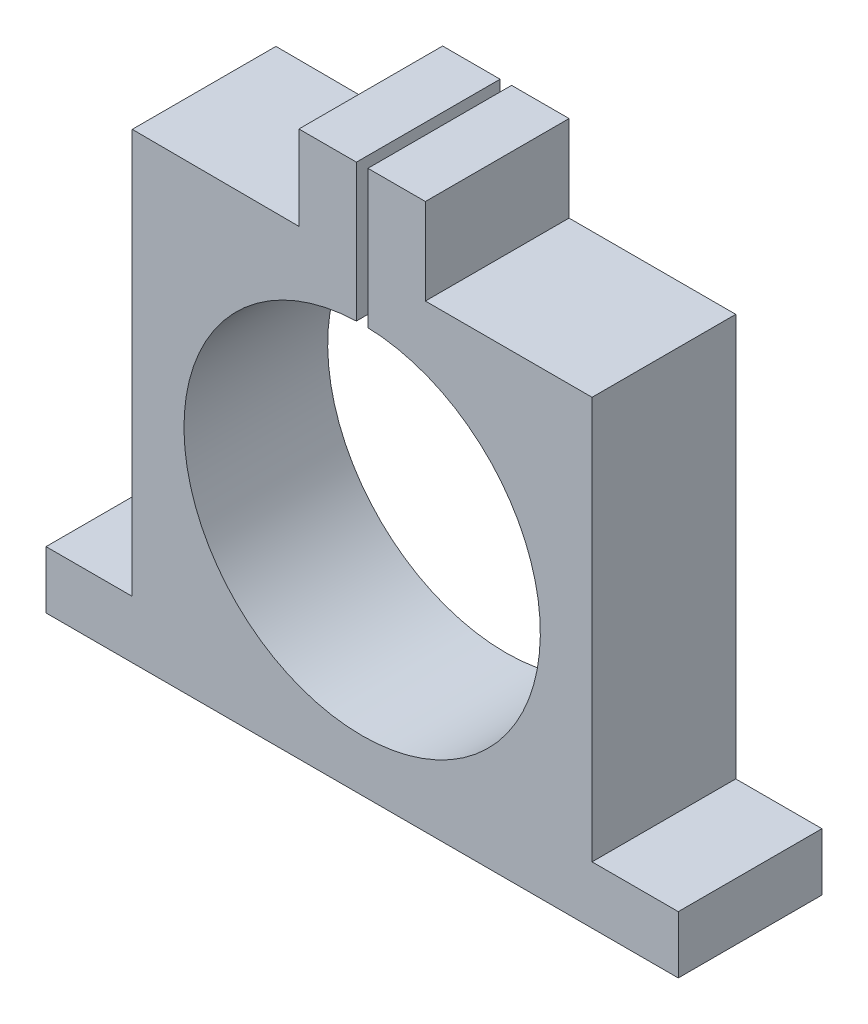
SolidWorks part; units mm, degrees
ref_plane "Alzado" through (0, 0, 0) normal (0, 0, 1) x (1, 0, 0)
ref_plane "Planta" through (0, 0, 0) normal (0, 1, 0) x (1, 0, 0)
ref_plane "Vista lateral" through (0, 0, 0) normal (1, 0, 0) x (0, 0, -1)
sketch "Croquis1" plane through (0, 0, 0) normal (0, 0, 1) x (1, 0, 0)
  line L0 (-103.4217, -38.5486) -> (6.5783, -38.5486)
  line L1 (6.5783, -38.5486) -> (6.5783, -28.5486)
  line L2 (6.5783, -28.5486) -> (-8.4217, -28.5486)
  line L3 (-8.4217, -28.5486) -> (-8.4217, 41.4514)
  line L4 (-8.4217, 41.4514) -> (-37.4217, 41.4514)
  line L5 (-37.4217, 41.4514) -> (-37.4217, 56.4514)
  line L6 (-37.4217, 56.4514) -> (-47.4217, 56.4514)
  line L7 (-47.4217, 56.4514) -> (-47.4217, 32.4353)
  line L9 (-49.4217, 56.3802) -> (-49.4217, 32.4353)
  line L10 (-49.4217, 56.3802) -> (-59.4217, 56.3802)
  line L11 (-59.4217, 56.3802) -> (-59.4217, 41.7047)
  line L12 (-59.4217, 41.7047) -> (-88.4217, 41.8246)
  line L13 (-88.4217, 41.8246) -> (-88.4217, -28.5486)
  line L14 (-88.4217, -28.5486) -> (-103.4217, -28.5486)
  line L15 (-103.4217, -28.5486) -> (-103.4217, -38.5486)
  line L17 (-48.4217, 60.914) -> (-48.4217, -23.4417) construction
  circle A0 centre (-48.4217, 1.4514) radius 31
  dimension "D3" = 95
  dimension "D7" = 40
  dimension "D1" = 10
  dimension "D2" = 15
  dimension "D4" = 80
  dimension "D5" = 15
  dimension "D6" = 110
  dimension "D8" = 29
  dimension "D9" = 29
  dimension "D10" = 10
  dimension "D11" = 10
extrude "Saliente-Extruir5" add sketch "Croquis1" along normal blind 25 contours A0 L9 L10 L11 L12 L13 L14 L15 L0 L1 L2 L3 L4 L5 L6 L7
